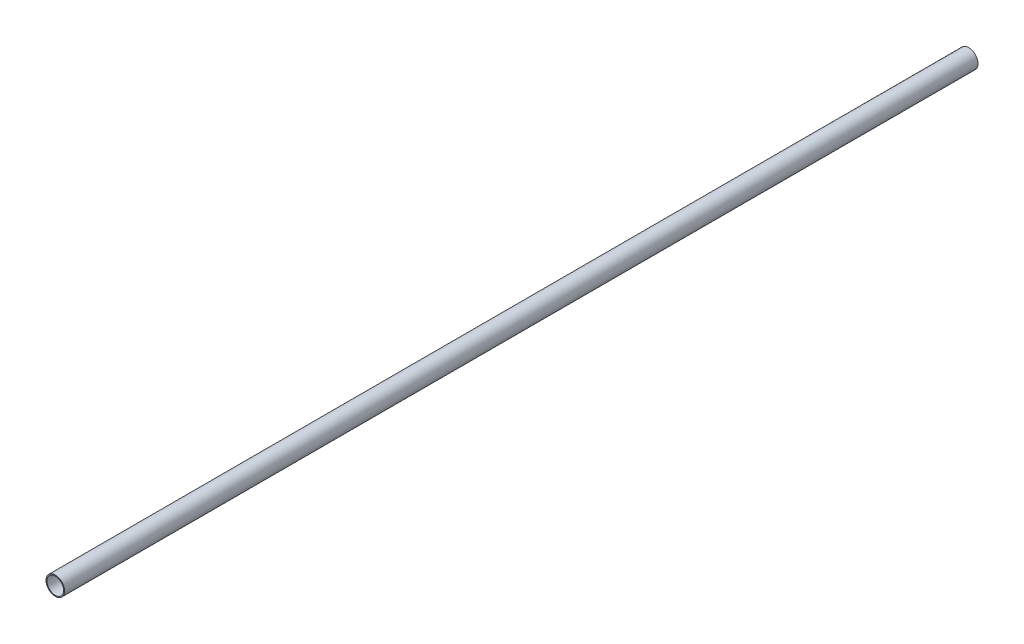
SolidWorks part; units mm, degrees
material "carbon fiber"
ref_plane "Front Plane" through (0, 0, 0) normal (0, 0, 1) x (1, 0, 0)
ref_plane "Top Plane" through (0, 0, 0) normal (0, 1, 0) x (1, 0, 0)
ref_plane "Right Plane" through (0, 0, 0) normal (1, 0, 0) x (0, 0, -1)
sketch "Эскиз1" plane through (0, 0, 0) normal (0, 0, 1) x (1, 0, 0)
  circle A0 centre (0, 0) radius 5
  circle A1 centre (0, 0) radius 4.5
  dimension "D1" = 10
  dimension "D2" = 0.5
extrude "Бобышка-Вытянуть1" add sketch "Эскиз1" along normal blind 492
